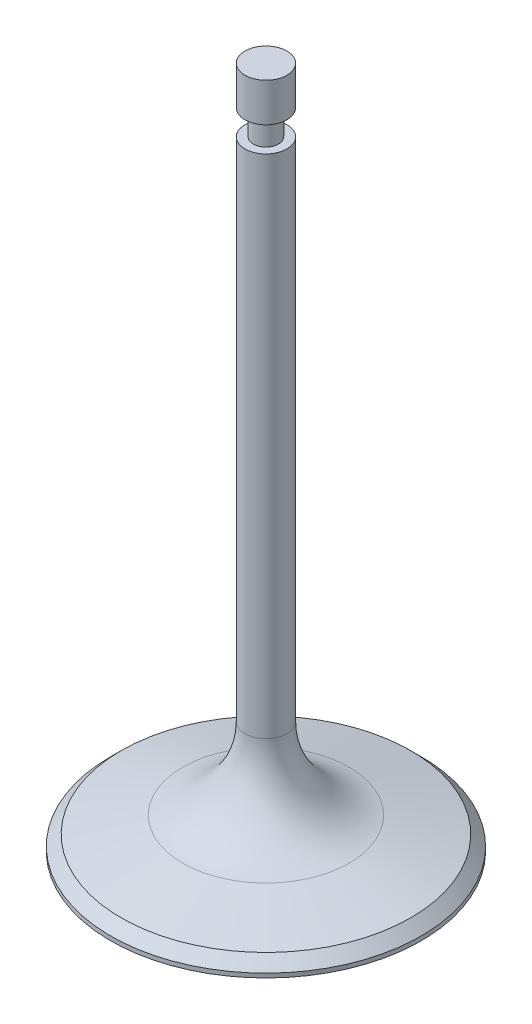
SolidWorks part; units mm, degrees
ref_plane "Front Plane" through (0, 0, 0) normal (0, 0, 1) x (1, 0, 0)
ref_plane "Top Plane" through (0, 0, 0) normal (0, 1, 0) x (1, 0, 0)
ref_plane "Right Plane" through (0, 0, 0) normal (1, 0, 0) x (0, 0, -1)
sketch "Sketch1" plane through (0, 0, 0) normal (0, 0, 1) x (1, 0, 0)
  line L0 (0, 7.6963) -> (0, 0) construction
  line L1 (0, 0) -> (18.5, 0) construction
  line L2 (18.5, -0.5) -> (18.5, 0)
  line L3 (18.5, 0) -> (17.25, 1.25)
  line L4 (17.25, 1.25) -> (9.9118, 3.2163)
  line L5 (2.5, 12.8755) -> (2.5, 73.19)
  line L6 (2.5, 73.19) -> (1.5, 73.19)
  line L7 (1.5, 73.19) -> (1.5, 76.19)
  line L8 (1.5, 76.19) -> (2.5, 76.19)
  line L9 (2.5, 76.19) -> (2.5, 80.79)
  line L10 (2.5, 80.79) -> (0, 80.79)
  line L11 (0, 80.79) -> (0, -2)
  arc A0 (0, -2) -> (18.5, -0.5) centre (0, 112.8333) ccw
  arc A1 (9.9118, 3.2163) -> (2.5, 12.8755) centre (12.5, 12.8755) cw
  dimension "D12" = 10
  dimension "D1" = 18.5
  dimension "D2" = 0.5
  dimension "D3" = 1.25
  dimension "D4" = 45
  dimension "D5" = 1.5
  dimension "D6" = 15
  dimension "D7" = 3
  dimension "D8" = 1
  dimension "D9" = 2.5
  dimension "D10" = 4.6
  dimension "D11" = 80.79
revolve "Revolve1" add sketch "Sketch1" angle 360 about L11
